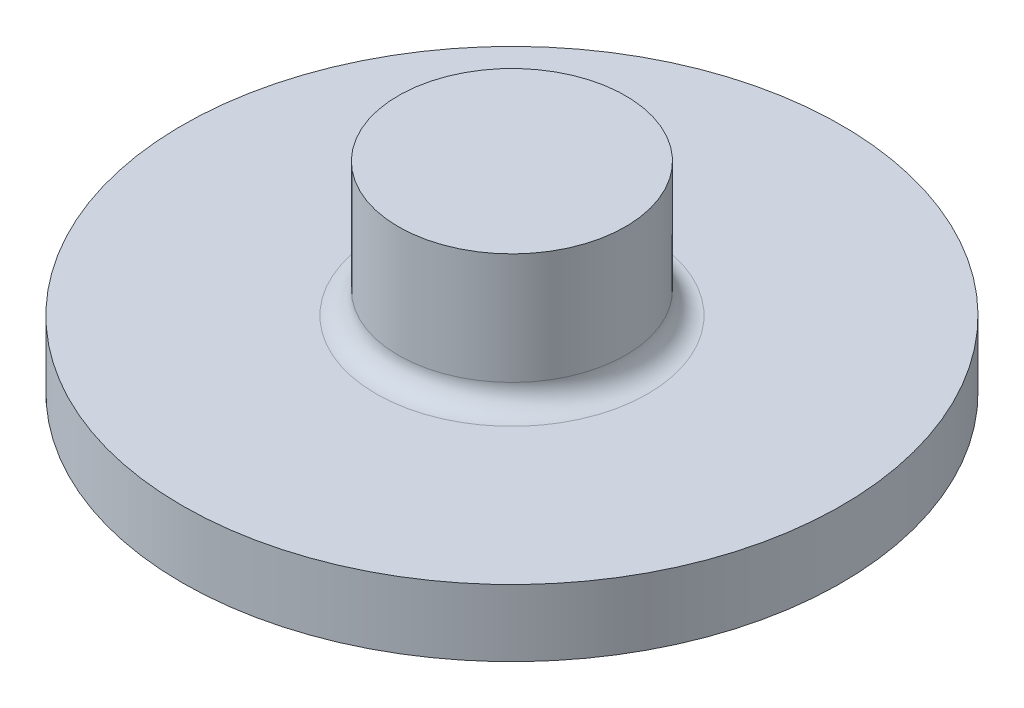
SolidWorks part; units mm, degrees
ref_plane "Front Plane" through (0, 0, 0) normal (0, 0, 1) x (1, 0, 0)
ref_plane "Top Plane" through (0, 0, 0) normal (0, 1, 0) x (1, 0, 0)
ref_plane "Right Plane" through (0, 0, 0) normal (1, 0, 0) x (0, 0, -1)
sketch "Sketch1" plane through (0, 0, 0) normal (0, 1, 0) x (1, 0, 0)
  circle A0 centre (0, 0) radius 7.4
  dimension "D1" = 14.8
extrude "Boss-Extrude1" add sketch "Sketch1" along normal blind 1.5 contours A0
sketch "Sketch2" plane through (0, 1.5, 0) normal (0, 1, 0) x (1, 0, 0)
  circle A0 centre (0, 0) radius 2.55
  dimension "D1" = 5.1
extrude "Boss-Extrude2" add sketch "Sketch2" along normal blind 3
fillet "Fillet1" radius 0.5 1 edges at (0, 1.5, 2.55)
